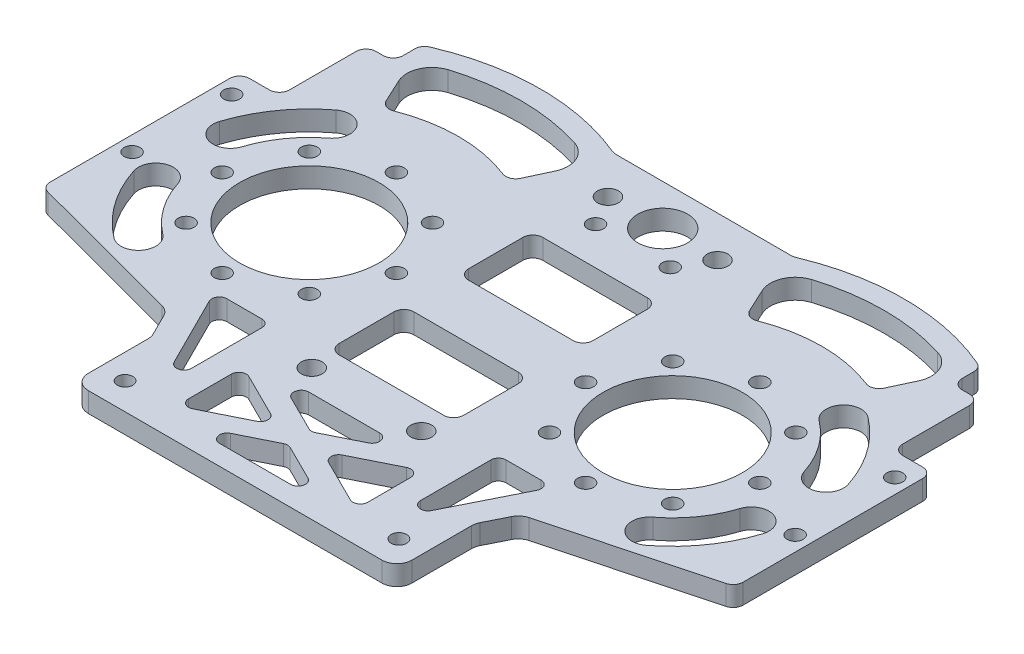
SolidWorks part; units mm, degrees
material "Thornel Mat VMA"
ref_plane "前视基准面" through (0, 0, 0) normal (0, 0, 1) x (1, 0, 0)
ref_plane "上视基准面" through (0, 0, 0) normal (0, 1, 0) x (1, 0, 0)
ref_plane "右视基准面" through (0, 0, 0) normal (1, 0, 0) x (0, 0, -1)
other "Configuration Table"
sketch "草图1" plane through (0, 0, 0) normal (0, 1, 0) x (1, 0, 0)
  line L0 (-36.5, 0) -> (36.5, 0) construction
  line L1 (-69.6, 36.5) -> (69.6, 36.5)
  line L2 (-69.6, 36.5) -> (-69.6, -36.5)
  line L3 (-69.6, -36.5) -> (69.6, -36.5)
  line L4 (69.6, 36.5) -> (69.6, -36.5)
  line L5 (-69.6, 36.5) -> (69.6, -36.5) construction
  line L6 (-69.6, -36.5) -> (69.6, 36.5) construction
  circle A0 centre (-36.5, 0) radius 14
  circle A1 centre (36.5, 0) radius 14
  point P0 (0, 0)
  point P10 (0, 0)
  dimension "D2" = 28
  dimension "D1" = 73
  dimension "D3" = 139.2
  dimension "D4" = 73
extrude "凸台-拉伸1" add sketch "草图1" along normal blind 4
sketch "草图2" plane through (0, 4, 0) normal (0, 1, 0) x (1, 0, 0)
  line L0 (0, -43.9683) -> (0, 35.9335) construction
  circle A0 centre (-36.5, 17.5) radius 1.6
  circle A1 centre (-36.5, 0) radius 17.5 construction
  circle A2 centre (-24.1256, 12.3744) radius 1.6
  circle A3 centre (-19, 0) radius 1.6
  circle A4 centre (-24.1256, -12.3744) radius 1.6
  circle A5 centre (-36.5, -17.5) radius 1.6
  circle A6 centre (-48.8744, -12.3744) radius 1.6
  circle A7 centre (-54, 0) radius 1.6
  circle A8 centre (-48.8744, 12.3744) radius 1.6
  circle A9 centre (36.5, 0) radius 17.5 construction
  circle A10 centre (48.8744, 12.3744) radius 1.6
  circle A11 centre (54, 0) radius 1.6
  circle A12 centre (48.8744, -12.3744) radius 1.6
  circle A13 centre (36.5, -17.5) radius 1.6
  circle A14 centre (24.1256, -12.3744) radius 1.6
  circle A15 centre (19, 0) radius 1.6
  circle A16 centre (24.1256, 12.3744) radius 1.6
  circle A17 centre (36.5, 17.5) radius 1.6
  point P24 (-36.5, 0)
  point P43 (36.5, 0)
  dimension "D1" = 3.2
  dimension "D2" = 35
  dimension "D3" = 8
extrude "切除-拉伸1" cut sketch "草图2" against normal blind 4
sketch "草图3" plane through (0, 4, 0) normal (0, 1, 0) x (1, 0, 0)
  line L0 (0, -14.2097) -> (0, 42.3316) construction
  circle A0 centre (66.6, -5.5) radius 1.6
  circle A1 centre (66.6, 14.5) radius 1.6
  circle A2 centre (-66.6, 14.5) radius 1.6
  circle A3 centre (-66.6, -5.5) radius 1.6
  circle A4 centre (11, -25) radius 2.1
  circle A5 centre (-11, -25) radius 2.1
  circle A6 centre (7.5, 28.5) radius 1.6
  circle A7 centre (-7.5, 28.5) radius 1.6
  dimension "D1" = 3.2
  dimension "D2" = 3.2
  dimension "D3" = 4.2
extrude "切除-拉伸2" cut sketch "草图3" against normal through all
sketch "草图7" plane through (0, 4, 0) normal (0, 1, 0) x (1, 0, 0)
  line L0 (36.5, 0) -> (16.8483, 42.1433) construction
  line L1 (36.5, 0) -> (36.5, 46.5) construction
  line L2 (36.5, 0) -> (56.1517, 42.1433) construction
  line L3 (56.1517, 42.1433) -> (56.1517, 36.5)
  line L4 (69.6, 36.5) -> (-69.6, 36.5) construction
  line L5 (16.8483, 42.1433) -> (16.8483, 36.5)
  line L6 (16.8483, 36.5) -> (56.1517, 36.5)
  line L7 (0, -85.5708) -> (0, 60.6628) construction
  line L8 (-16.8483, 36.5) -> (-56.1517, 36.5)
  line L9 (-56.1517, 42.1433) -> (-56.1517, 36.5)
  line L10 (-16.8483, 42.1433) -> (-16.8483, 36.5)
  circle A0 centre (36.5, 0) radius 30 construction
  circle A1 centre (36.5, 0) radius 42.5 construction
  circle A2 centre (36.5, 0) radius 46.5
  circle A3 centre (-36.5, 0) radius 46.5
  line M28 (69.6, 36.5) -> (-69.6, 36.5)
  dimension "D1" = 60
  dimension "D2" = 85
  dimension "D3" = 93
  dimension "D4" = 50
extrude "凸台-拉伸2" add sketch "草图7" against normal blind 4 contours L3 A2 L5 M28 | A3 L9 L10 M28
sketch "草图8" plane through (0, 4, 0) normal (0, 1, 0) x (1, 0, 0)
  line L0 (61.6, 36.5) -> (61.6, 19.1)
  line L1 (61.6, 19.1) -> (69.6, 19.1)
  line L2 (69.6, -36.5) -> (69.6, 36.5) construction
  line L3 (69.6, 19.1) -> (69.6, 36.5)
  line L4 (69.6, 36.5) -> (61.6, 36.5)
  line L5 (36.5, 0) -> (16.8483, 42.1433) construction
  line L6 (36.5, 0) -> (56.1517, 42.1433) construction
  line L7 (23.8215, 27.1892) -> (18.5387, 38.5181)
  line L8 (49.1785, 27.1892) -> (54.4613, 38.5181)
  line L9 (0, -85.5708) -> (0, 60.6628) construction
  line L10 (0, -85.5708) -> (0, 60.6628) construction
  line L11 (-49.1785, 27.1892) -> (-54.4613, 38.5181)
  line L12 (-23.8215, 27.1892) -> (-18.5387, 38.5181)
  line L13 (-69.6, 36.5) -> (-61.6, 36.5)
  line L14 (-69.6, 19.1) -> (-69.6, 36.5)
  line L15 (-61.6, 19.1) -> (-69.6, 19.1)
  line L16 (-61.6, 36.5) -> (-61.6, 19.1)
  circle A0 centre (36.5, 0) radius 42.5 construction
  circle A1 centre (36.5, 0) radius 30 construction
  arc A2 (54.4613, 38.5181) -> (18.5387, 38.5181) centre (36.5, 0) ccw
  arc A3 (49.1785, 27.1892) -> (23.8215, 27.1892) centre (36.5, 0) ccw
  circle A4 centre (66.6, 14.5) radius 1.6 construction
  arc A5 (-49.1785, 27.1892) -> (-23.8215, 27.1892) centre (-36.5, 0) cw
  arc A6 (-54.4613, 38.5181) -> (-18.5387, 38.5181) centre (-36.5, 0) cw
  dimension "D1" = 3
  dimension "D2" = 8
extrude "切除-拉伸3" cut sketch "草图8" against normal blind 4
sketch "草图10" plane through (0, 4, 0) normal (0, 1, 0) x (1, 0, 0)
  line L0 (69.6, -20.5) -> (9.6, -36.5)
  line L1 (-12.5, 20.9) -> (12.5, 20.9)
  line L2 (-12.5, 20.9) -> (-12.5, 6)
  line L3 (-12.5, 6) -> (12.5, 6)
  line L4 (12.5, 20.9) -> (12.5, 6)
  line L5 (-12.5, -5) -> (12.5, -5)
  line L6 (-12.5, -5) -> (-12.5, -20)
  line L7 (-12.5, -20) -> (12.5, -20)
  line L8 (12.5, -5) -> (12.5, -20)
  line L9 (69.6, -36.5) -> (69.6, 19.1) construction
  line L10 (69.6, -20.5) -> (73.6, -20.5) construction
  line L11 (-69.6, -36.5) -> (69.6, -36.5) construction
  line L12 (9.6, -36.5) -> (69.6, -36.5)
  line L13 (69.6, -36.5) -> (69.6, -20.5)
  line L14 (0, -48.8838) -> (0, 53.7833) construction
  line L15 (-69.6, -36.5) -> (-69.6, -20.5)
  line L16 (-9.6, -36.5) -> (-69.6, -36.5)
  line L17 (-69.6, -20.5) -> (-9.6, -36.5)
  circle A0 centre (7.5, 28.5) radius 1.6 construction
  point P18 (0, -5)
  point P20 (0, 6)
  dimension "D1" = 25
  dimension "D2" = 25
  dimension "D3" = 6
  dimension "D4" = 11
  dimension "D5" = 5
  dimension "D6" = 15
  dimension "D7" = 60
extrude "切除-拉伸4" cut sketch "草图10" against normal blind 4
fillet "圆角2" radius 5 4 edges at (54.4613, 2, -38.5181) (18.5387, 2, -38.5181) (-18.5387, 2, -38.5181) (-54.4613, 2, -38.5181)
fillet "圆角3" radius 2 30 edges at (9.6, 2, 36.5) (69.6, 2, 20.5) (69.6, 2, -19.1) (61.6, 2, -19.1) (61.6, 2, -36.5) (56.1517, 2, -36.5) (56.1517, 2, -42.1433) (16.8483, 2, -42.1433) (16.8483, 2, -36.5) (-16.8483, 2, -36.5) (-16.8483, 2, -42.1433) (-56.1517, 2, -42.1433) (-56.1517, 2, -36.5) (-61.6, 2, -36.5) (-61.6, 2, -19.1) (-69.6, 2, -19.1) (-69.6, 2, 20.5) (-9.6, 2, 36.5) (-23.8215, 2, -27.1892) (-49.1785, 2, -27.1892) (49.1785, 2, -27.1892) (23.8215, 2, -27.1892) (12.5, 2, 5) (12.5, 2, 20) (-12.5, 2, 20) (-12.5, 2, 5) (12.5, 2, -20.9) (12.5, 2, -6) (-12.5, 2, -6) (-12.5, 2, -20.9)
sketch "草图11" plane through (0, 4, 0) normal (0, 1, 0) x (1, 0, 0)
  line L1 (-18.0549, 42.6852) -> (18.0549, 42.6852)
  line L2 (-18.0549, 42.6852) -> (-18.0549, 36.5)
  line L3 (-18.0549, 36.5) -> (18.0549, 36.5)
  line L4 (18.0549, 42.6852) -> (18.0549, 36.5)
  line L5 (14.8483, 36.5) -> (-14.8483, 36.5) construction
extrude "凸台-拉伸3" add sketch "草图11" against normal blind 4
sketch "草图12" plane through (0, 4, 0) normal (0, 1, 0) x (1, 0, 0)
  circle A0 centre (11, 34.5) radius 2.1
  circle A1 centre (-11, 34.5) radius 2.1
  dimension "D1" = 4.2
extrude "切除-拉伸5" cut sketch "草图12" against normal blind 4
sketch "草图13" plane through (0, 0, 0) normal (0, -1, 0) x (1, 0, 0)
  line L0 (-32.5, 30.3933) -> (-32.5, 51.3933)
  line L1 (-9.8532, 36.4325) -> (-68.1153, 20.8959) construction
  line L2 (-32.5, 51.3933) -> (32.5, 51.3933)
  line L3 (32.5, 51.3933) -> (32.5, 30.3933)
  line L4 (68.1153, 20.8959) -> (9.8532, 36.4325) construction
  line L5 (32.5, 30.3933) -> (-32.5, 30.3933)
  circle A0 centre (-27.5, 46) radius 1.55 construction
  circle A1 centre (-27.5, 46) radius 1.55
  circle A2 centre (27.5, 46) radius 1.55 construction
  circle A3 centre (27.5, 46) radius 1.55
  point P8 (0, 30.3933)
  dimension "D1" = 65
  dimension "D2" = 21
extrude "凸台-拉伸4" add sketch "草图13" against normal blind 4
sketch "草图14" plane through (0, 0, 0) normal (0, -1, 0) x (1, 0, 0)
  line L0 (-23, 43.5) -> (-34, 21.5)
  line L1 (-34, 21.5) -> (-23, 21.5)
  line L2 (-23, 21.5) -> (-23, 43.5)
  line L3 (0, 0) -> (0, 14.2718) construction
  line L4 (-18, 47.3933) -> (18, 47.3933)
  line L5 (-18, 47.3933) -> (-18, 29.5)
  line L6 (-18, 29.5) -> (18, 29.5)
  line L7 (18, 47.3933) -> (18, 29.5)
  line L8 (32.5, 51.3933) -> (-32.5, 51.3933) construction
  line L9 (34, 21.5) -> (23, 21.5)
  line L10 (23, 43.5) -> (34, 21.5)
  line L11 (23, 21.5) -> (23, 43.5)
  circle A0 centre (0, -34.5) radius 5
  circle A1 centre (11, -34.5) radius 2.1 construction
  circle A2 centre (11, -34.5) radius 2.1 construction
  circle A3 centre (11, 25) radius 2.1 construction
  circle A5 centre (-36.5, 17.5) radius 1.6 construction
  point P15 (0, 29.5)
  dimension "D1" = 10
  dimension "D2" = 4
  dimension "D3" = 4.5
  dimension "D4" = 5
  dimension "D5" = 4
  dimension "D6" = 34
  dimension "D7" = 11
  dimension "D8" = 22
extrude "切除-拉伸6" cut sketch "草图14" against normal blind 4
sketch "草图15" plane through (0, 0, 0) normal (0, -1, 0) x (1, 0, 0)
  line L0 (-18, 47.3933) -> (18, 29.5)
  line L1 (-18, 29.5) -> (18, 47.3933)
extrude "拉伸-薄壁1" add sketch "草图15" against normal blind 4 thin thin type mid plane wall 4
sketch "草图16" plane through (0, 0, 0) normal (0, -1, 0) x (1, 0, 0)
  line L0 (-35.5502, 29.5799) -> (-32.5, 35.6803)
  line L1 (-32.5, 30.3933) -> (-68.1153, 20.8959) construction
  line L2 (-32.5, 51.3933) -> (-32.5, 30.3933) construction
  line L3 (-23, 43.5) -> (-34, 21.5) construction
  line L4 (-32.5, 30.3933) -> (-68.1153, 20.8959) construction
  line L5 (-32.5, 51.3933) -> (-32.5, 30.3933) construction
  line L6 (-32.5, 30.3933) -> (-35.5502, 29.5799)
  line L7 (-32.5, 35.6803) -> (-32.5, 30.3933)
  line L8 (0, 0) -> (0, 14.3476) construction
  line L9 (32.5, 35.6803) -> (32.5, 30.3933)
  line L10 (32.5, 30.3933) -> (35.5502, 29.5799)
  line L11 (35.5502, 29.5799) -> (32.5, 35.6803)
  dimension "D1" = 5
extrude "凸台-拉伸5" add sketch "草图16" against normal blind 4
fillet "圆角5" radius 1.5 18 edges at (34, 2, 21.5) (23, 2, 21.5) (23, 2, 43.5) (-23, 2, 21.5) (-23, 2, 43.5) (0, 2, 40.6801) (-13.5065, 2, 47.3933) (13.5065, 2, 47.3933) (4.4935, 2, 38.4467) (18, 2, 45.1599) (18, 2, 31.7334) (-4.4935, 2, 38.4467) (-18, 2, 31.7334) (-18, 2, 45.1599) (-13.5065, 2, 29.5) (0, 2, 36.2132) (13.5065, 2, 29.5) (-34, 2, 21.5)
fillet "圆角6" radius 3 8 edges at (32.5, 2, 35.6803) (32.5, 2, 51.3933) (-32.5, 2, 51.3933) (-32.5, 2, 35.6803) (-18.0549, 2, -42.6852) (18.0549, 2, -42.6852) (35.5502, 2, 29.5799) (-35.5502, 2, 29.5799)
sketch "草图17" plane through (0, 0, 0) normal (0, -1, 0) x (1, 0, 0)
  line L0 (0, -51.2524) -> (0, 14.1094) construction
  circle A0 centre (-36.5, 0) radius 24.5 construction
  arc A1 (-51.3324, 19.5) -> (-59.8238, 7.5) centre (-36.5, 0) ccw construction
  arc A2 (-53.4513, 22.2857) -> (-63.1558, 8.5714) centre (-36.5, 0) ccw
  arc A3 (-49.2135, 16.7143) -> (-56.4918, 6.4286) centre (-36.5, 0) ccw
  arc A4 (-49.2135, 16.7143) -> (-53.4513, 22.2857) centre (-51.3324, 19.5) ccw
  arc A5 (-63.1558, 8.5714) -> (-56.4918, 6.4286) centre (-59.8238, 7.5) ccw
  arc A6 (-59.8238, -7.5) -> (-51.3324, -19.5) centre (-36.5, 0) ccw construction
  arc A7 (-63.1558, -8.5714) -> (-53.4513, -22.2857) centre (-36.5, 0) ccw
  arc A8 (-56.4918, -6.4286) -> (-49.2135, -16.7143) centre (-36.5, 0) ccw
  arc A9 (-56.4918, -6.4286) -> (-63.1558, -8.5714) centre (-59.8238, -7.5) ccw
  arc A10 (-53.4513, -22.2857) -> (-49.2135, -16.7143) centre (-51.3324, -19.5) ccw
  arc A11 (51.3324, 19.5) -> (59.8238, 7.5) centre (36.5, 0) cw construction
  arc A12 (53.4513, 22.2857) -> (63.1558, 8.5714) centre (36.5, 0) cw
  arc A13 (49.2135, 16.7143) -> (56.4918, 6.4286) centre (36.5, 0) cw
  arc A14 (49.2135, 16.7143) -> (53.4513, 22.2857) centre (51.3324, 19.5) cw
  arc A15 (63.1558, 8.5714) -> (56.4918, 6.4286) centre (59.8238, 7.5) cw
  arc A16 (59.8238, -7.5) -> (51.3324, -19.5) centre (36.5, 0) cw construction
  arc A17 (63.1558, -8.5714) -> (53.4513, -22.2857) centre (36.5, 0) cw
  arc A18 (56.4918, -6.4286) -> (49.2135, -16.7143) centre (36.5, 0) cw
  arc A19 (56.4918, -6.4286) -> (63.1558, -8.5714) centre (59.8238, -7.5) cw
  arc A20 (53.4513, -22.2857) -> (49.2135, -16.7143) centre (51.3324, -19.5) cw
  circle A21 centre (36.5, 0) radius 24.5 construction
  point P5 (-56.4993, 14.1519)
  point P13 (-56.4993, -14.1519)
  point P24 (56.4993, 14.1519)
  point P32 (56.4993, -14.1519)
  dimension "D1" = 49
  dimension "D4" = 3.5
  dimension "D2" = 15
  dimension "D3" = 7.5
  dimension "D5" = 12
  dimension "D6" = 12
extrude "切除-拉伸7" cut sketch "草图17" against normal blind 4
